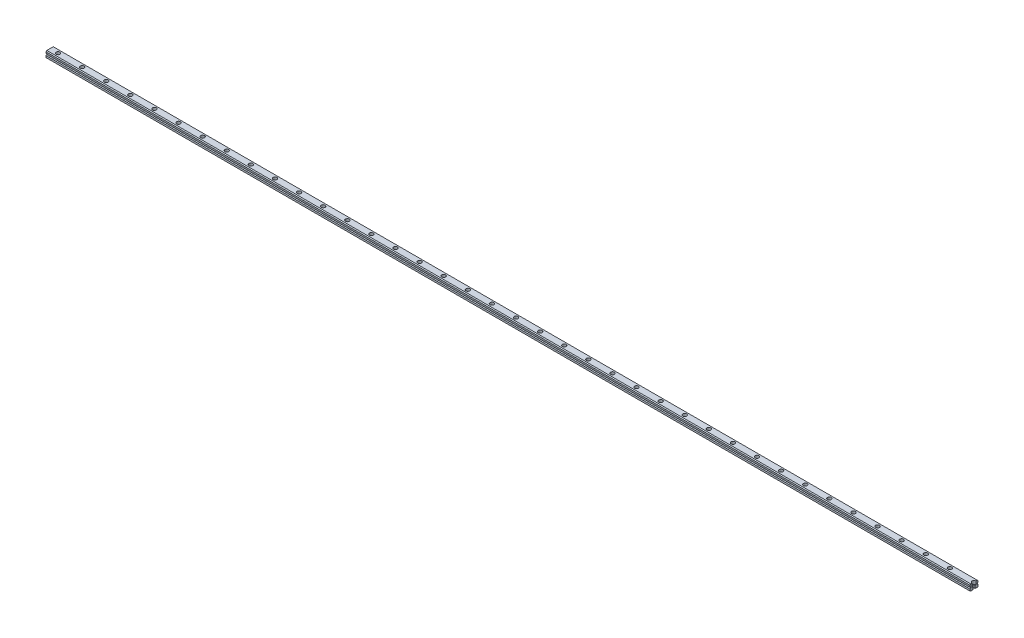
SolidWorks part; units mm, degrees
material "201 Annealed Stainless Steel (SS)"
ref_plane "Front Plane" through (0, 0, 0) normal (0, 0, 1) x (1, 0, 0)
ref_plane "Top Plane" through (0, 0, 0) normal (0, 1, 0) x (1, 0, 0)
ref_plane "Right Plane" through (0, 0, 0) normal (1, 0, 0) x (0, 0, -1)
sketch "Sketch1" plane through (0, 0, 0) normal (1, 0, 0) x (0, 0, -1)
  line L0 (0, 39.5089) -> (0, 0) construction
  line L1 (9, 0) -> (-9, 0)
  line L2 (-9, 0) -> (-10, 1)
  line L3 (-10, 1) -> (-10, 5.5)
  line L4 (-10, 5.5) -> (-8, 7)
  line L5 (-8, 7) -> (-8, 8.5)
  line L6 (-8, 8.5) -> (-10, 10.5)
  line L7 (-10, 10.5) -> (-10, 13.5)
  line L8 (-10, 13.5) -> (-8, 15.5)
  line L9 (-8, 15.5) -> (8, 15.5)
  line L10 (-18.0832, 7.75) -> (13.0406, 7.75) construction
  line L11 (-4.25, 15.5) -> (-4.25, 7) construction
  line L12 (-4.25, 7) -> (-3, 7) construction
  line L13 (-3, 7) -> (-3, 0) construction
  line L14 (4.25, 15.5) -> (4.25, 7) construction
  line L15 (4.25, 7) -> (3, 7) construction
  line L16 (3, 7) -> (3, 0) construction
  line L17 (9, 0) -> (10, 1)
  line L18 (10, 1) -> (10, 5.5)
  line L19 (10, 5.5) -> (8, 7)
  line L20 (8, 7) -> (8, 8.5)
  line L21 (8, 8.5) -> (10, 10.5)
  line L22 (10, 13.5) -> (8, 15.5)
  line L23 (10, 10.5) -> (10, 13.5)
  point P14 (-8, 7.75)
  point P32 (0, 15.5)
  dimension "D1" = 10
  dimension "D2" = 1
  dimension "D3" = 1
  dimension "D4" = 5.5
  dimension "D5" = 7.75
  dimension "D6" = 15.5
  dimension "D7" = 4.25
  dimension "D8" = 3
  dimension "D9" = 8.5
  dimension "D10" = 7
  dimension "D11" = 2
  dimension "D12" = 2
  dimension "D13" = 2
  dimension "D14" = 2
extrude "Boss-Extrude1" add sketch "Sketch1" along normal blind 2300
sketch "Sketch2" plane through (0, 15.5, 0) normal (0, 1, 0) x (1, 0, 0)
  line L0 (0, 0) -> (2300, 0) construction
  line L1 (0, 8) -> (0, -8) construction
  line L2 (2300, 8) -> (2300, -8) construction
  circle A0 centre (20, 0) radius 4.75
  dimension "D1" = 9.5
  dimension "D2" = 20
extrude "Cut-Extrude1" cut sketch "Sketch2" against normal blind 8.5
sketch "Sketch3" plane through (0, 7, 0) normal (0, 1, 0) x (1, 0, 0)
  circle A0 centre (20, 0) radius 3
  dimension "D1" = 6
extrude "Cut-Extrude2" cut sketch "Sketch3" against normal through all
pattern_linear "LPattern1" count 40 spacing 60 along (1, 0, 0) of "Cut-Extrude2", "Cut-Extrude1"
